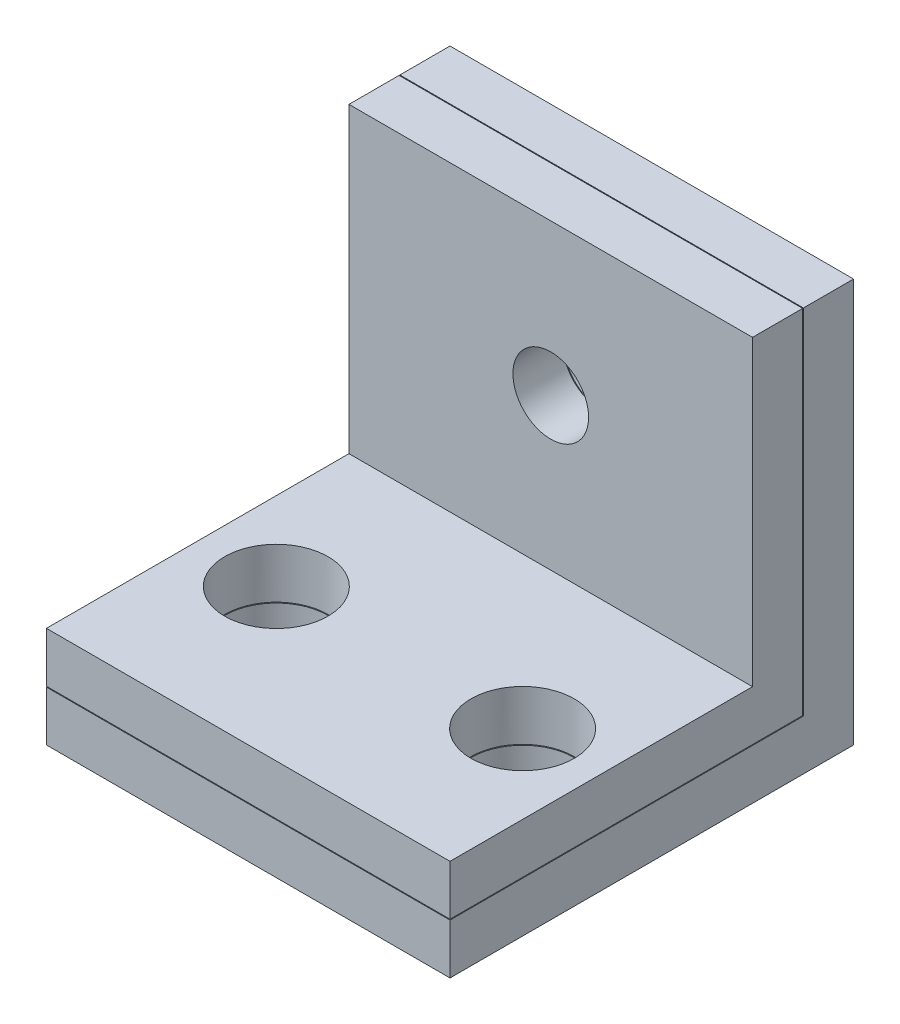
SolidWorks part; units mm, degrees
ref_plane "Alzado" through (0, 0, 0) normal (0, 0, 1) x (1, 0, 0)
ref_plane "Planta" through (0, 0, 0) normal (0, 1, 0) x (1, 0, 0)
ref_plane "Vista lateral" through (0, 0, 0) normal (1, 0, 0) x (0, 0, -1)
sketch "Croquis1" plane through (0, 0, 0) normal (1, 0, 0) x (0, 0, -1)
  line L0 (0, 0) -> (50.8, 0)
  line L1 (50.8, 0) -> (50.8, 50.8)
  line L2 (0, 6.31) -> (44.49, 6.31)
  line L3 (44.49, 6.31) -> (44.49, 50.8)
  line L4 (0, 6.31) -> (0, 0)
  line L5 (44.49, 50.8) -> (50.8, 50.8)
  dimension "D1" = 50.8
  dimension "D2" = 50.8
  dimension "D3" = 6.31
extrude "Saliente-Extruir1" add sketch "Croquis1" along normal blind 50.8
sketch "Croquis2" plane through (50.8, 0, 0) normal (1, 0, 0) x (0, 0, -1)
  line L0 (0, 6.41) -> (44.39, 6.41)
  line L1 (44.39, 6.41) -> (44.39, 50.8)
  line L3 (0, 6.31) -> (0, 9.7762) construction
  line L4 (44.49, 50.8) -> (44.39, 50.8) construction
  line L5 (0, 12.72) -> (38.08, 12.72)
  line L6 (38.08, 12.72) -> (38.08, 50.8)
  line L7 (0, 12.72) -> (0, 6.41)
  line L8 (38.08, 50.8) -> (44.39, 50.8)
  line L9 (44.49, 6.31) -> (0, 6.31) construction
  line L10 (44.49, 50.8) -> (44.49, 6.31) construction
  dimension "D2" = 0.1
  dimension "D3" = 0.1
  dimension "D1" = 6.31
extrude "Saliente-Extruir2" add sketch "Croquis2" against normal blind 50.8 separate body
sketch "Croquis4" plane through (0, 12.72, 0) normal (0, 1, 0) x (1, 0, 0)
  line L0 (0, 19.04) -> (50.8, 19.04) construction
  line L1 (0, 38.08) -> (0, 0) construction
  line L2 (50.8, 38.08) -> (50.8, 0) construction
  line L3 (25.4, 19.04) -> (25.4, 30.6742) construction
  circle A0 centre (9.9, 19.04) radius 6.5
  circle A1 centre (40.9, 19.04) radius 6.5
  dimension "D1" = 13
  dimension "D2" = 13
  dimension "D3" = 15.5
  dimension "D4" = 15.5
extrude "Cortar-Extruir1" cut sketch "Croquis4" against normal blind 97.8
sketch "Croquis5" plane through (0, 0, -38.08) normal (0, 0, 1) x (1, 0, 0)
  line L0 (0, 50.8) -> (0, 12.72) construction
  line L1 (0, 12.72) -> (0, 31.76) construction
  line L2 (0, 31.76) -> (50.8, 31.76) construction
  line L3 (50.8, 50.8) -> (50.8, 12.72) construction
  line L4 (50.8, 31.76) -> (25.4, 31.76) construction
  line L5 (25.4, 31.76) -> (25.4, 50.8) construction
  line L6 (0, 50.8) -> (50.8, 50.8) construction
  circle A0 centre (25.4, 31.76) radius 4.7625
  dimension "D1" = 9.525
extrude "Cortar-Extruir2" cut sketch "Croquis5" against normal blind 25
